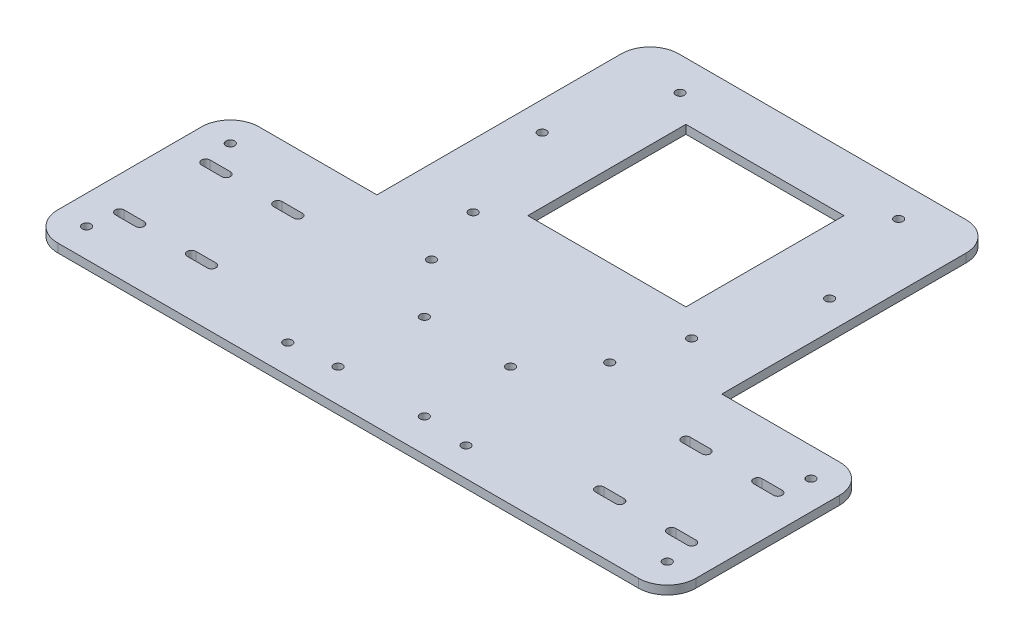
SolidWorks part; units mm, degrees
ref_plane "Front Plane" through (0, 0, 0) normal (0, 0, 1) x (1, 0, 0)
ref_plane "Top Plane" through (0, 0, 0) normal (0, 1, 0) x (1, 0, 0)
ref_plane "Right Plane" through (0, 0, 0) normal (1, 0, 0) x (0, 0, -1)
sketch "Sketch1" plane through (0, 0, 0) normal (0, 1, 0) x (1, 0, 0)
  line L0 (-60, 130) -> (60, 130)
  line L1 (60, 130) -> (60, 35)
  line L2 (60, 35) -> (111, 35)
  line L3 (111, 35) -> (111, -35)
  line L4 (111, -35) -> (-111, -35)
  line L5 (0, 130) -> (0, -35) construction
  line L6 (-111, 0) -> (111, 0) construction
  line L7 (74.5, -16.5) -> (67.5, -16.5)
  line L8 (96, 15) -> (71, 15) construction
  line L9 (96, 15) -> (96, -15) construction
  line L10 (96, -15) -> (71, -15) construction
  line L11 (71, 15) -> (71, -15) construction
  line L12 (83.5, -15) -> (83.5, 15) construction
  line L13 (96, 0) -> (71, 0) construction
  line L14 (74.5, 13.5) -> (67.5, 13.5)
  line L15 (74.5, 13.5) -> (74.5, 16.5) construction
  line L16 (74.5, 16.5) -> (67.5, 16.5)
  line L17 (67.5, 13.5) -> (67.5, 16.5) construction
  line L18 (71, 16.5) -> (71, 13.5) construction
  line L19 (74.5, 15) -> (67.5, 15) construction
  line L20 (74.5, -13.5) -> (67.5, -13.5)
  line L21 (92.5, 15) -> (99.5, 15) construction
  line L22 (96, 16.5) -> (96, 13.5) construction
  line L23 (99.5, 13.5) -> (99.5, 16.5) construction
  line L24 (92.5, 13.5) -> (92.5, 16.5) construction
  line L25 (92.5, 16.5) -> (99.5, 16.5)
  line L26 (92.5, 13.5) -> (99.5, 13.5)
  line L27 (92.5, -13.5) -> (99.5, -13.5)
  line L28 (92.5, -16.5) -> (99.5, -16.5)
  line L29 (-92.5, 13.5) -> (-92.5, 16.5) construction
  line L30 (-99.5, 13.5) -> (-99.5, 16.5) construction
  line L31 (-96, 16.5) -> (-96, 13.5) construction
  line L32 (-92.5, 15) -> (-99.5, 15) construction
  line L33 (-74.5, 15) -> (-67.5, 15) construction
  line L34 (-71, 16.5) -> (-71, 13.5) construction
  line L35 (-67.5, 13.5) -> (-67.5, 16.5) construction
  line L36 (-74.5, 13.5) -> (-74.5, 16.5) construction
  line L37 (-96, 0) -> (-71, 0) construction
  line L38 (-83.5, -15) -> (-83.5, 15) construction
  line L39 (-71, 15) -> (-71, -15) construction
  line L40 (-96, -15) -> (-71, -15) construction
  line L41 (-96, 15) -> (-96, -15) construction
  line L42 (-96, 15) -> (-71, 15) construction
  line L43 (-92.5, -16.5) -> (-99.5, -16.5)
  line L44 (-92.5, -13.5) -> (-99.5, -13.5)
  line L45 (-92.5, 13.5) -> (-99.5, 13.5)
  line L46 (-92.5, 16.5) -> (-99.5, 16.5)
  line L47 (-74.5, -13.5) -> (-67.5, -13.5)
  line L48 (-74.5, 16.5) -> (-67.5, 16.5)
  line L49 (-74.5, 13.5) -> (-67.5, 13.5)
  line L50 (-74.5, -16.5) -> (-67.5, -16.5)
  line L51 (-111, 35) -> (-111, -35)
  line L52 (-60, 35) -> (-111, 35)
  line L53 (-60, 130) -> (-60, 35)
  line L55 (-27.5, 110) -> (27.5, 110)
  line L56 (-27.5, 110) -> (-27.5, 55)
  line L57 (-27.5, 55) -> (27.5, 55)
  line L58 (27.5, 110) -> (27.5, 55)
  line L59 (0, 55) -> (0, 110) construction
  line L60 (-27.5, 82.5) -> (27.5, 82.5) construction
  line L61 (-38, 46.5) -> (38, 46.5) construction
  line L62 (-38, 46.5) -> (-38, 118.5) construction
  line L63 (-38, 118.5) -> (38, 118.5) construction
  line L64 (38, 46.5) -> (38, 118.5) construction
  line L65 (0, 118.5) -> (0, 46.5) construction
  line L66 (-38, 82.5) -> (38, 82.5) construction
  line L67 (15, -23.5) -> (-15, -23.5) construction
  line L68 (15, -23.5) -> (15, 6.5) construction
  line L69 (15, 6.5) -> (-15, 6.5) construction
  line L70 (-15, -23.5) -> (-15, 6.5) construction
  line L71 (0, 6.5) -> (0, -23.5) construction
  line L72 (15, -8.5) -> (-15, -8.5) construction
  arc A1 (74.5, 16.5) -> (74.5, 13.5) centre (74.5, 15) cw
  arc A2 (67.5, 16.5) -> (67.5, 13.5) centre (67.5, 15) ccw
  arc A3 (67.5, -16.5) -> (67.5, -13.5) centre (67.5, -15) cw
  arc A4 (74.5, -16.5) -> (74.5, -13.5) centre (74.5, -15) ccw
  arc A5 (99.5, 16.5) -> (99.5, 13.5) centre (99.5, 15) cw
  arc A6 (92.5, 16.5) -> (92.5, 13.5) centre (92.5, 15) ccw
  arc A7 (92.5, -16.5) -> (92.5, -13.5) centre (92.5, -15) cw
  arc A8 (99.5, -16.5) -> (99.5, -13.5) centre (99.5, -15) ccw
  arc A9 (-99.5, -16.5) -> (-99.5, -13.5) centre (-99.5, -15) cw
  arc A10 (-92.5, -16.5) -> (-92.5, -13.5) centre (-92.5, -15) ccw
  arc A11 (-92.5, 16.5) -> (-92.5, 13.5) centre (-92.5, 15) cw
  arc A12 (-99.5, 16.5) -> (-99.5, 13.5) centre (-99.5, 15) ccw
  arc A13 (-74.5, -16.5) -> (-74.5, -13.5) centre (-74.5, -15) cw
  arc A14 (-67.5, -16.5) -> (-67.5, -13.5) centre (-67.5, -15) ccw
  arc A15 (-67.5, 16.5) -> (-67.5, 13.5) centre (-67.5, 15) cw
  arc A16 (-74.5, 16.5) -> (-74.5, 13.5) centre (-74.5, 15) ccw
  circle A17 centre (38, 118.5) radius 1.5
  circle A18 centre (38, 46.5) radius 1.5
  circle A19 centre (-38, 118.5) radius 1.5
  circle A20 centre (-38, 46.5) radius 1.5
  circle A21 centre (-15, 6.5) radius 1.5
  circle A22 centre (15, 6.5) radius 1.5
  circle A23 centre (15, -23.5) radius 1.5
  circle A24 centre (-15, -23.5) radius 1.5
  circle A25 centre (-50, 82.5) radius 1.5
  circle A26 centre (-101, 25) radius 1.5
  circle A27 centre (-101, -25) radius 1.5
  circle A28 centre (-31, 25) radius 1.5
  circle A29 centre (-31, -25) radius 1.5
  circle A30 centre (101, 25) radius 1.5
  circle A31 centre (101, -25) radius 1.5
  circle A32 centre (31, -25) radius 1.5
  circle A33 centre (31, 25) radius 1.5
  circle A34 centre (50, 82.5) radius 1.5
  point P9 (83.5, 0)
  point P66 (0, 0)
  point P82 (-83.5, 0)
  point P83 (0, 82.5)
  point P91 (0, 82.5)
  point P92 (0, -8.5)
  dimension "D6" = 7
  dimension "D9" = 3
  dimension "D11" = 3
  dimension "D19" = 3
  dimension "D20" = 3
  dimension "D1" = 25
  dimension "D2" = 30
  dimension "D3" = 71
  dimension "D4" = 15
  dimension "D5" = 20
  dimension "D7" = 3
  dimension "D8" = 76
  dimension "D10" = 30
  dimension "D12" = 55
  dimension "D13" = 55
  dimension "D14" = 8.5
  dimension "D15" = 55
  dimension "D16" = 40
  dimension "D17" = 20
  dimension "D18" = 120
  dimension "D21" = 10
  dimension "D22" = 10
  dimension "D23" = 10
  dimension "D24" = 80
extrude "Boss-Extrude1" add sketch "Sketch1" along normal blind 3
fillet "Fillet1" radius 10 6 edges at (-60, 1.5, -130) (60, 1.5, -130) (111, 1.5, -35) (111, 1.5, 35) (-111, 1.5, 35) (-111, 1.5, -35)
